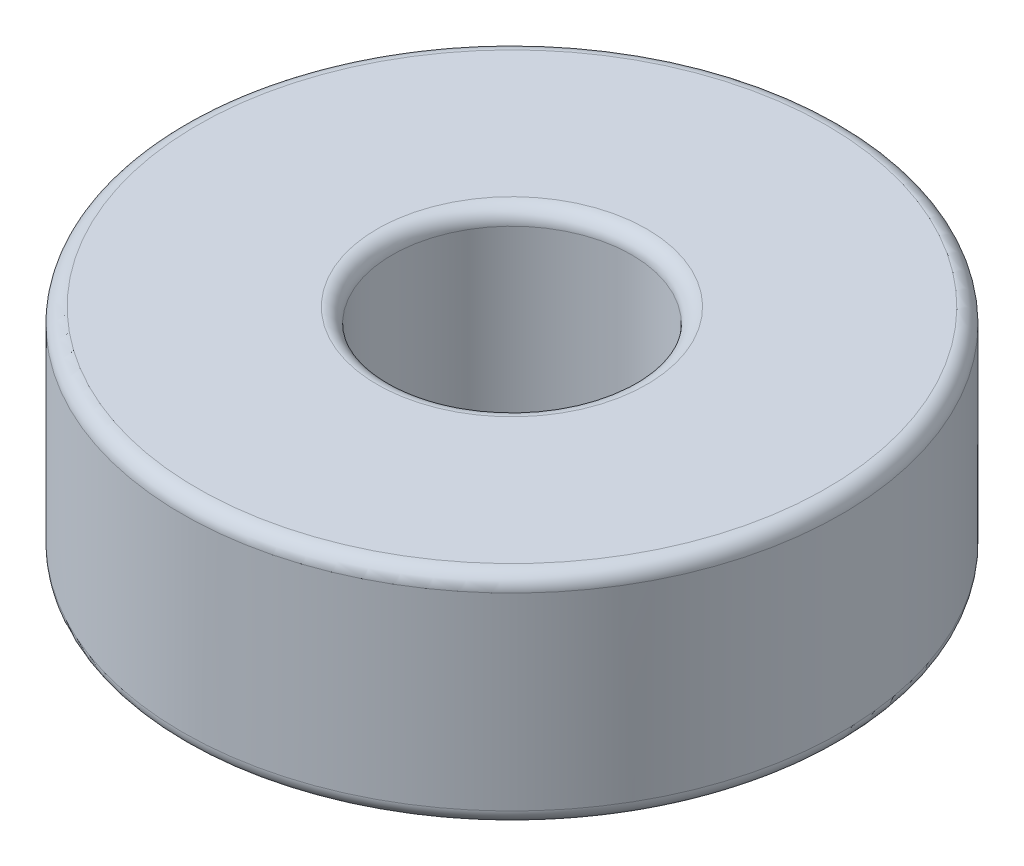
SolidWorks part; units mm, degrees
ref_plane "Front Plane" through (0, 0, 0) normal (0, 0, 1) x (1, 0, 0)
ref_plane "Top Plane" through (0, 0, 0) normal (0, 1, 0) x (1, 0, 0)
ref_plane "Right Plane" through (0, 0, 0) normal (1, 0, 0) x (0, 0, -1)
sketch "Sketch1" plane through (0, 0, 0) normal (0, 0, 1) x (1, 0, 0)
  line L0 (0, 0) -> (0, 19.9651) construction
  line L2 (-4, 0) -> (-11, 0)
  line L3 (-4, 0) -> (-4, 7.3)
  line L4 (-4, 7.3) -> (-11, 7.3)
  line L5 (-11, 0) -> (-11, 7.3)
  dimension "D1" = 7.3
  dimension "D2" = 4
  dimension "D3" = 11
revolve "Revolve1" add sketch "Sketch1" angle 360 about L0
fillet "Fillet1" radius 0.5 4 edges at (0, 0, -4) (0, 0, -11) (0, 7.3, -4) (0, 7.3, -11)
